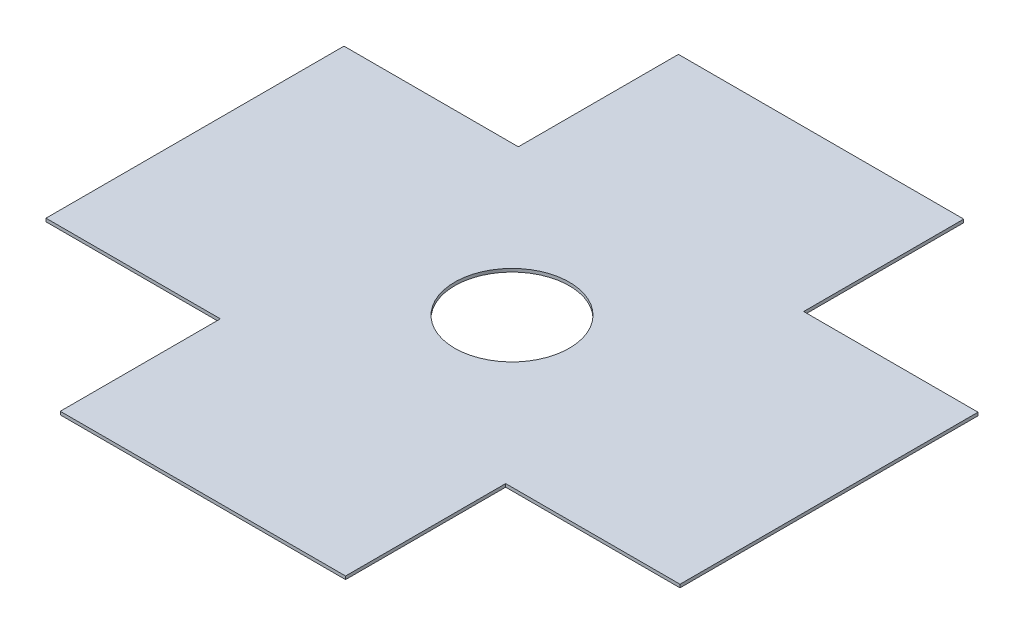
SolidWorks part; units mm, degrees
ref_plane "Front Plane" through (0, 0, 0) normal (0, 0, 1) x (1, 0, 0)
ref_plane "Top Plane" through (0, 0, 0) normal (0, 1, 0) x (1, 0, 0)
ref_plane "Right Plane" through (0, 0, 0) normal (1, 0, 0) x (0, 0, -1)
ref_plane "Plane1" through (0, -167, 0) normal (0, -1, 0) x (1, 0, 0)
sketch "Sketch1" plane through (0, -167, 0) normal (0, -1, 0) x (1, 0, 0)
  line L0 (279.2999, -275.4209) -> (389.2999, -275.4209)
  line L1 (389.2999, -275.4209) -> (389.2999, -87.4209)
  line L2 (389.2999, -87.4209) -> (279.2999, -87.4209)
  line L3 (279.2999, -87.4209) -> (279.2999, 13.5791)
  line L4 (279.2999, 13.5791) -> (99.2999, 13.5791)
  line L5 (99.2999, 13.5791) -> (99.2999, -87.4209)
  line L6 (99.2999, -87.4209) -> (-10.7001, -87.4209)
  line L7 (-10.7001, -87.4209) -> (-10.7001, -275.4209)
  line L8 (-10.7001, -275.4209) -> (99.2999, -275.4209)
  line L9 (99.2999, -275.4209) -> (99.2999, -376.4209)
  line L10 (99.2999, -376.4209) -> (279.2999, -376.4209)
  line L11 (279.2999, -376.4209) -> (279.2999, -275.4209)
  line L12 (-10.7001, -181.4209) -> (389.2999, -181.4209) construction
  line L13 (189.2999, -376.4209) -> (189.2999, 13.5791) construction
  dimension "D1" = 195
  dimension "D2" = 195
  dimension "D3" = 180
  dimension "D4" = 200
  dimension "D5" = 200
  dimension "D6" = 188
extrude "Boss-Extrude1" add sketch "Sketch1" against normal blind 2
sketch "Sketch2" plane through (0, -165, 0) normal (0, 1, 0) x (1, 0, 0)
  line L0 (279.2999, -13.5791) -> (99.2999, -13.5791) construction
  line L1 (-10.7001, 87.4209) -> (-10.7001, 275.4209) construction
  circle A0 centre (189.2999, 181.4209) radius 36.15
  dimension "D1" = 72.3
  dimension "D2" = 195
  dimension "D3" = 200
extrude "Cut-Extrude1" cut sketch "Sketch2" against normal through all
sketch "Sketch3" plane through (0, -167, 0) normal (0, -1, 0) x (1, 0, 0)
  line L0 (-10.7001, -181.4209) -> (421.7654, -181.4209) construction
  line L1 (-10.7001, -87.4209) -> (-10.7001, -275.4209) construction
  line L2 (99.2999, 13.5791) -> (99.2999, -87.4209) construction
  circle A0 centre (99.2999, -110.9525) radius 10
  circle A1 centre (279.2999, -109.6415) radius 10
  circle A2 centre (279.2999, -253.2003) radius 10
  circle A3 centre (99.2999, -251.8893) radius 10
  dimension "D1" = 180
extrude "Boss-Extrude2" add sketch "Sketch3" along normal blind 10
